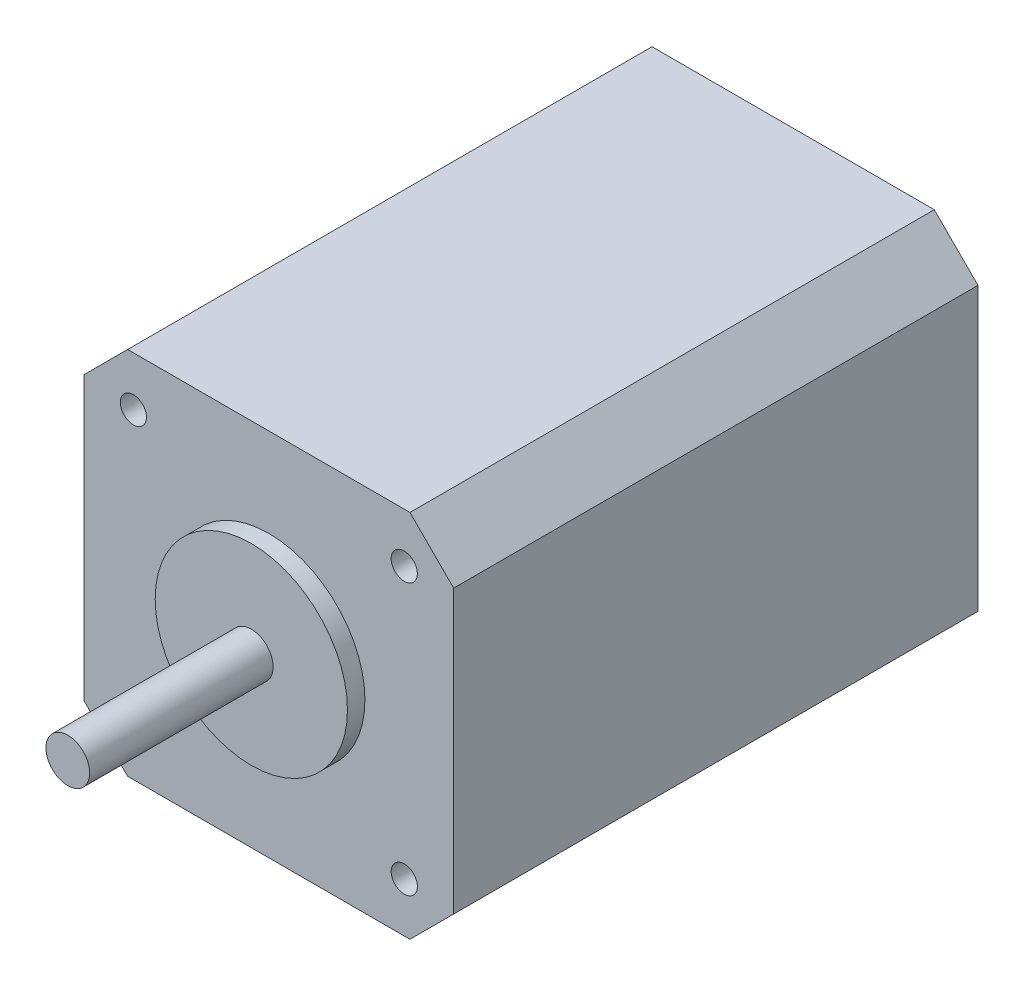
SolidWorks part; units mm, degrees
ref_plane "Alzado" through (0, 0, 0) normal (0, 0, 1) x (1, 0, 0)
ref_plane "Planta" through (0, 0, 0) normal (0, 1, 0) x (1, 0, 0)
ref_plane "Vista lateral" through (0, 0, 0) normal (1, 0, 0) x (0, 0, -1)
sketch "Croquis1" plane through (0, 0, 0) normal (0, 0, 1) x (1, 0, 0)
  line L0 (0, 21.15) -> (0, -21.15) construction
  line L1 (21.15, 21.15) -> (-21.15, 21.15)
  line L2 (21.15, 21.15) -> (21.15, -21.15)
  line L3 (21.15, -21.15) -> (-21.15, -21.15)
  line L4 (-21.15, 21.15) -> (-21.15, -21.15)
  line L5 (21.15, 21.15) -> (-21.15, -21.15) construction
  line L6 (21.15, -21.15) -> (-21.15, 21.15) construction
  line L7 (-21.15, 0) -> (21.15, 0) construction
  circle A0 centre (-15.5, 15.5) radius 1.5
  circle A1 centre (-15.5, -15.5) radius 1.5
  circle A2 centre (15.5, -15.5) radius 1.5
  circle A3 centre (15.5, 15.5) radius 1.5
  point P0 (0, 0)
  point P14 (0, 0)
  point P15 (0, 0)
  point P16 (0, 0)
  dimension "D3" = 3
  dimension "D1" = 42.3
  dimension "D2" = 42.3
  dimension "D4" = 15.5
  dimension "D5" = 15.5
extrude "Saliente-Extruir1" add sketch "Croquis1" along normal mid plane 60
sketch "Croquis2" plane through (0, 0, 30) normal (0, 0, 1) x (1, 0, 0)
  circle A0 centre (0, 0) radius 11
  dimension "D1" = 22
extrude "Saliente-Extruir2" add sketch "Croquis2" along normal blind 2
sketch "Croquis3" plane through (0, 0, 30) normal (0, 0, 1) x (1, 0, 0)
  circle A0 centre (0, 0) radius 2.5
  dimension "D1" = 5
extrude "Saliente-Extruir3" add sketch "Croquis3" along normal blind 23
chamfer "Chaflán1" distance 5 angle 45 4 edges at (-21.15, -21.15, 0) (21.15, -21.15, 0) (-21.15, 21.15, 0) (21.15, 21.15, 0)
